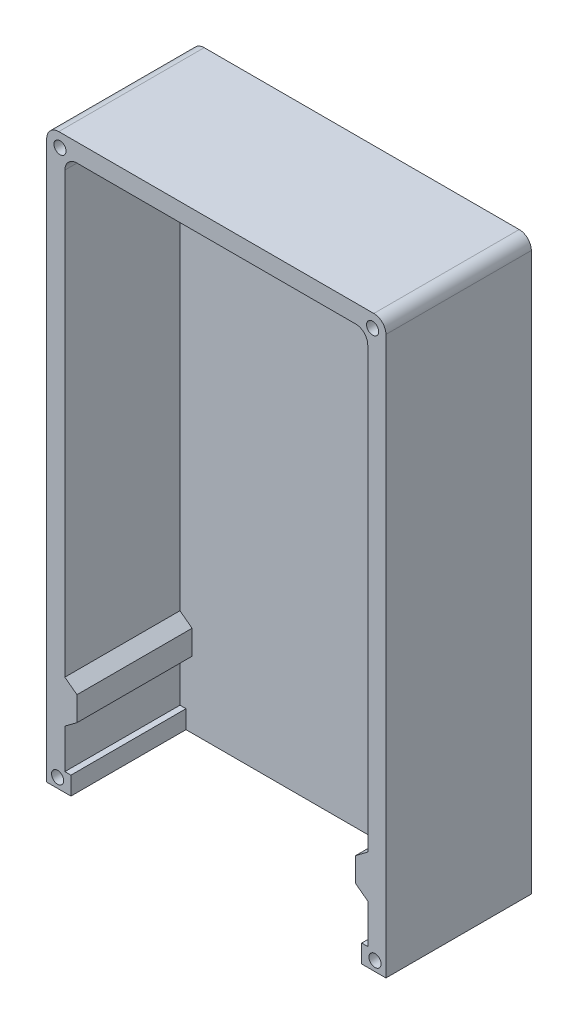
SolidWorks part; units mm, degrees
ref_plane "Ebene vorne" through (0, 0, 0) normal (0, 0, 1) x (1, 0, 0)
ref_plane "Ebene oben" through (0, 0, 0) normal (0, 1, 0) x (1, 0, 0)
ref_plane "Ebene rechts" through (0, 0, 0) normal (1, 0, 0) x (0, 0, -1)
sketch "Skizze1" plane through (0, 0, 0) normal (0, 0, 1) x (1, 0, 0)
  line L0 (0, 0) -> (0, 47)
  line L1 (0, 47) -> (28, 47)
  line L2 (28, 47) -> (28, 0)
  line L3 (28, 0) -> (0, 0)
  dimension "D1" = 47
  dimension "D2" = 28
extrude "Aufsatz-Linear austragen1" add sketch "Skizze1" along normal blind 12
sketch "Skizze2" plane through (0, 0, 12) normal (0, 0, 1) x (1, 0, 0)
  line L0 (0, 47) -> (0, 0) construction
  line L1 (2.5, 45.5) -> (25.5, 45.5)
  line L2 (1.5, 44.5) -> (1.5, 8.2519)
  line L3 (1.5, 1.5) -> (2, 1.5)
  line L4 (26.5, 44.5) -> (26.5, 8.2519)
  line L5 (28, 47) -> (0, 47) construction
  line L6 (28, 0) -> (28, 47) construction
  line L7 (0, 0) -> (28, 0) construction
  line L8 (26, 1.5) -> (26.5, 1.5)
  line L10 (2, 1.5) -> (2, 0)
  line L12 (26, 1.5) -> (26, 0)
  line L13 (2, 0) -> (26, 0)
  line L14 (26.5, 8.2519) -> (25.5, 7.5)
  line L15 (25.5, 7.5) -> (25.5, 5.5)
  line L16 (25.5, 5.5) -> (26.5, 4.7519)
  line L17 (26.5, 4.7519) -> (26.5, 1.5)
  line L18 (14, 0) -> (14, 53.6399) construction
  line L19 (2.5, 5.5) -> (1.5, 4.7519)
  line L20 (2.5, 7.5) -> (2.5, 5.5)
  line L21 (1.5, 8.2519) -> (2.5, 7.5)
  line L22 (1.5, 4.7519) -> (1.5, 1.5)
  line L23 (-12.8344, 23.5) -> (47.2834, 23.5) construction
  arc A0 (25.5, 45.5) -> (26.5, 44.5) centre (25.5, 44.5) cw
  arc A1 (2.5, 45.5) -> (1.5, 44.5) centre (2.5, 44.5) ccw
  point P22 (25.5, 6.5)
  point P39 (1.2235, 45.7877)
  point P40 (0, 0)
  dimension "D6" = 1
  dimension "D1" = 1.5
  dimension "D2" = 1.5
  dimension "D3" = 1.5
  dimension "D4" = 1.5
  dimension "D5" = 24
  dimension "D7" = 2
  dimension "D8" = 1
  dimension "D9" = 3.5
  dimension "D10" = 126.8
  dimension "D11" = 6.5
  dimension "D15" = 23.5
extrude "Schnitt-Linear austragen1" cut sketch "Skizze2" against normal blind 9.5
fillet "Verrundung2" radius 1 2 edges at (0, 47, 6) (28, 47, 6)
sketch "Skizze3" plane through (0, 0, 12) normal (0, 0, 1) x (1, 0, 0)
  line L1 (26, 0) -> (28, 0) construction
  line L2 (28, 0) -> (28, 46) construction
  line L4 (0, 46) -> (0, 0) construction
  line L6 (27, 47) -> (1, 47) construction
  line L7 (0, 0) -> (2, 0) construction
  circle A0 centre (1.1, 45.9) radius 0.5
  circle A1 centre (26.9, 45.9) radius 0.5
  circle A2 centre (0.9, 0.8) radius 0.5
  circle A3 centre (27.1, 0.8) radius 0.5
  point P24 (-0.7113, 46.1857)
  point P25 (0, 0)
  dimension "D1" = 1
  dimension "D2" = 1
  dimension "D3" = 1
  dimension "D4" = 1
  dimension "D11" = 1.1
  dimension "D5" = 0.8
  dimension "D6" = 0.9
  dimension "D7" = 0.8
  dimension "D8" = 0.9
  dimension "D9" = 1.1
  dimension "D10" = 1.1
  dimension "D12" = 1.1
extrude "Schnitt-Linear austragen2" cut sketch "Skizze3" against normal blind 3
